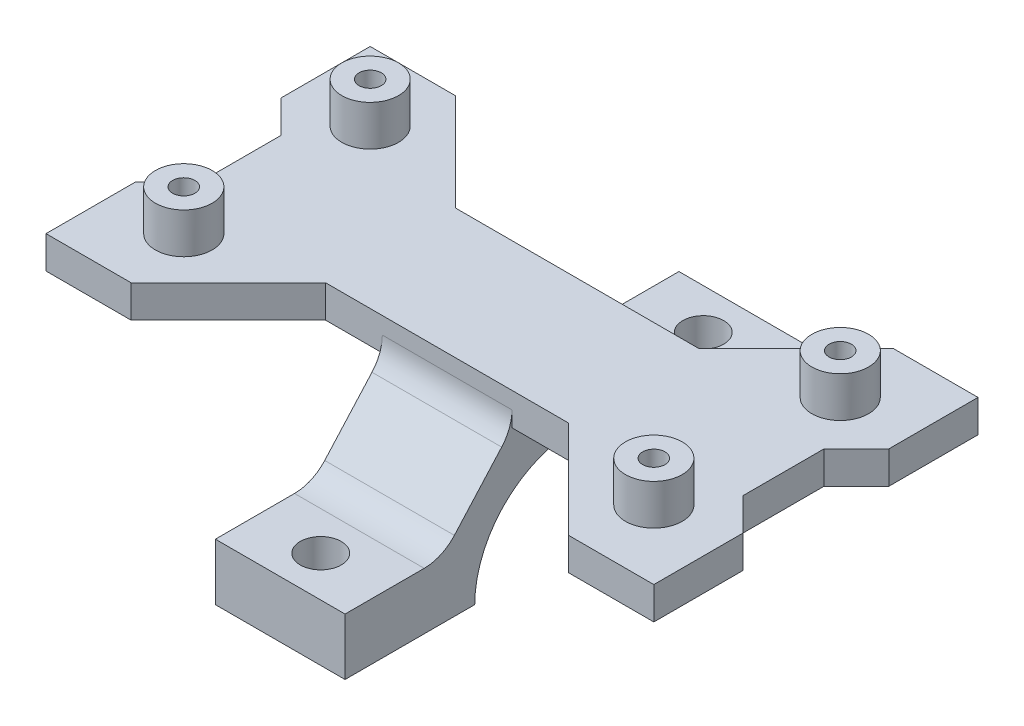
SolidWorks part; units mm, degrees
ref_plane "Front Plane" through (0, 0, 0) normal (0, 0, 1) x (1, 0, 0)
ref_plane "Top Plane" through (0, 0, 0) normal (0, 1, 0) x (1, 0, 0)
ref_plane "Right Plane" through (0, 0, 0) normal (1, 0, 0) x (0, 0, -1)
sketch "Sketch1" plane through (0, 0, 0) normal (0, 1, 0) x (1, 0, 0)
  line L0 (0, 0) -> (0, -93.1614) construction
  line L1 (37.5, 20) -> (37.5, 9)
  line L2 (37.5, 20) -> (27, 20)
  line L3 (-37.5, 20) -> (-37.5, 9)
  line L4 (37.5, -20) -> (27, -20)
  line L5 (37.5, 20) -> (-37.5, -20) construction
  line L6 (-37.5, 20) -> (37.5, -20) construction
  line L13 (0, 0) -> (-28.6286, 0) construction
  line L15 (15, 8) -> (-15, 8)
  line L18 (-27, 20) -> (-37.5, 20)
  line L19 (15, 8) -> (27, 20)
  line L20 (-27, 20) -> (-15, 8)
  line L21 (15, -8) -> (27, -20)
  line L22 (15, -8) -> (-15, -8)
  line L23 (-27, -20) -> (-15, -8)
  line L24 (-27, -20) -> (-37.5, -20)
  line L25 (37.5, 9) -> (33.5, 5)
  line L26 (33.5, 5) -> (33.5, -5)
  line L27 (33.5, -5) -> (37.5, -9)
  line L28 (37.5, -9) -> (37.5, -20)
  line L29 (-37.5, 9) -> (-33.5, 5)
  line L30 (-33.5, 5) -> (-33.5, -5)
  line L31 (-33.5, -5) -> (-37.5, -9)
  line L32 (-37.5, -9) -> (-37.5, -20)
  circle A2 centre (-29, -11.5) radius 1.375
  circle A4 centre (-29, 11.5) radius 1.375
  circle A5 centre (29, -11.5) radius 1.375
  circle A6 centre (29, 11.5) radius 1.375
  point P0 (0, 0)
  point P7 (0, -8)
  point P40 (-33.5, 0)
  dimension "D3" = 30
  dimension "D4" = 12
  dimension "D5" = 45
  dimension "D6" = 2.75
  dimension "D7" = 8.5
  dimension "D8" = 8.5
  dimension "D1" = 75
  dimension "D2" = 40
  dimension "D9" = 45
  dimension "D11" = 10
  dimension "D10" = 4
  dimension "D12" = 135
extrude "Mount_Plate" add sketch "Sketch1" along normal blind 4
sketch "Sketch2" plane through (0, 0, 0) normal (0, -1, 0) x (1, 0, 0)
  line L0 (0, 12.5) -> (0, -12.5) construction
  point P4 (0, 0)
  dimension "D1" = 25
sketch "Sketch4" plane through (0, 0, 0) normal (1, 0, 0) x (0, 0, -1)
  line L3 (-16.6, -9.6) -> (-28.6, -9.6)
  line L9 (-28.6, -9.6) -> (-28.6, -16.6)
  line L10 (-28.6, -16.6) -> (-12.6, -16.6)
  line L11 (0, 0) -> (0, -35.0008) construction
  line L12 (28.6, -16.6) -> (12.6, -16.6)
  line L13 (28.6, -9.6) -> (28.6, -16.6)
  line L14 (16.6, -9.6) -> (28.6, -9.6)
  line L15 (-8, 0) -> (8, 0)
  line L17 (-16.6, -9.6) -> (-8, 0)
  line L19 (16.6, -9.6) -> (8, 0)
  arc A0 (12.6, -16.6) -> (-12.6, -16.6) centre (0, -16.6) ccw
  point P3 (0, 0)
  point P15 (0, -4)
  dimension "D1" = 25.2
  dimension "D2" = 12
  dimension "D3" = 7
  dimension "D6" = 16
  dimension "D4" = 16
  dimension "D5" = 4
extrude "Feuselage_Mount" add sketch "Sketch4" along normal mid plane 16
sketch "Sketch8" plane through (0, 4, 0) normal (0, 1, 0) x (1, 0, 0)
  line L0 (0, 0) -> (0, -11.8748) construction
  line L1 (0, 0) -> (11.5, 0) construction
  circle A0 centre (29, -11.5) radius 1.375
  circle A1 centre (-29, -11.5) radius 1.375 construction
  circle A2 centre (29, -11.5) radius 3.5
  circle A3 centre (-29, 11.5) radius 3.5
  circle A5 centre (-29, -11.5) radius 1.375
  circle A9 centre (-29, -11.5) radius 3.5
  circle A10 centre (-29, 11.5) radius 1.375
  circle A11 centre (29, 11.5) radius 3.5
  circle A12 centre (29, 11.5) radius 1.375
  dimension "D1" = 7
extrude "Mounting_Holes" add sketch "Sketch8" along normal blind 5
sketch "Sketch10" plane through (0, -16.6, 0) normal (0, -1, 0) x (1, 0, 0)
  line L0 (0, 0) -> (0, 43.6015) construction
  line L1 (0, 0) -> (30.4685, 0) construction
  line L2 (8, 28.6) -> (-8, 28.6) construction
  circle A0 centre (0, 23.6) radius 2.525
  circle A1 centre (0, -23.6) radius 2.525
  point P8 (0, 23.6)
  dimension "D1" = 5.05
  dimension "D3" = 5
extrude "Fastening_Holes" cut sketch "Sketch10" against normal blind 8 and the other way through all
fillet "Fillet1" radius 5 4 edges at (0, -9.6, -16.6) (0, -9.6, 16.6) (0, 0, -8) (0, 0, 8)
